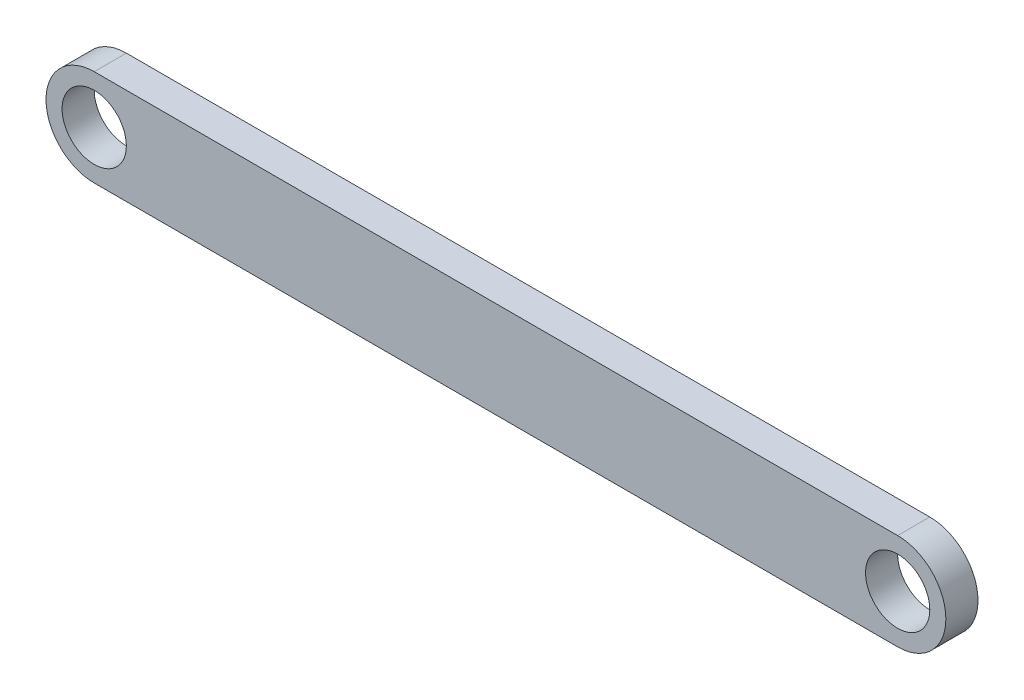
SolidWorks part; units mm, degrees
ref_plane "Спереди" through (0, 0, 0) normal (0, 0, 1) x (1, 0, 0)
ref_plane "Сверху" through (0, 0, 0) normal (0, 1, 0) x (1, 0, 0)
ref_plane "Справа" through (0, 0, 0) normal (1, 0, 0) x (0, 0, -1)
other "Configuration Table"
sketch "Эскиз1" plane through (0, 0, 0) normal (0, 0, 1) x (1, 0, 0)
  line L0 (0, 0) -> (250, 0) construction
  line L1 (0, 15) -> (250, 15)
  line L2 (0, -15) -> (250, -15)
  arc A0 (0, 15) -> (0, -15) centre (0, 0) ccw
  arc A1 (250, -15) -> (250, 15) centre (250, 0) ccw
  circle A2 centre (0, 0) radius 10
  circle A3 centre (250, 0) radius 10
  point P3 (125, 0)
  dimension "D1" = 250
  dimension "D2" = 30
extrude "Бобышка-Вытянуть1" add sketch "Эскиз1" along normal blind 10
